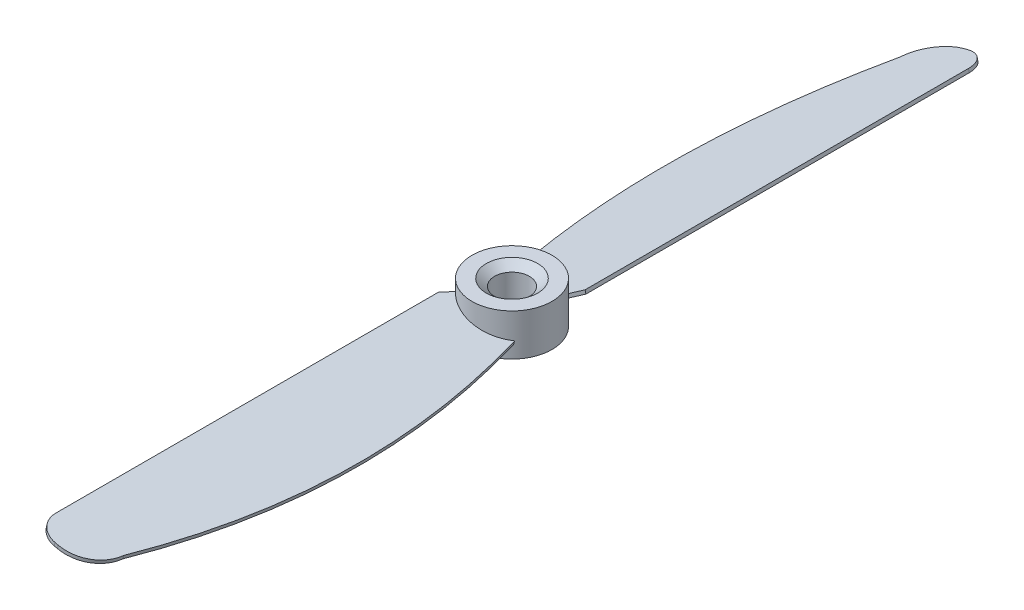
SolidWorks part; units mm, degrees
ref_plane "前视基准面" through (0, 0, 0) normal (0, 0, 1) x (1, 0, 0)
ref_plane "上视基准面" through (0, 0, 0) normal (0, 1, 0) x (1, 0, 0)
ref_plane "右视基准面" through (0, 0, 0) normal (1, 0, 0) x (0, 0, -1)
sketch "草图1" plane through (0, 0, 0) normal (0, 1, 0) x (1, 0, 0)
  circle A0 centre (0, 0) radius 5.75
  dimension "D1" = 11.5
extrude "凸台-拉伸1" add sketch "草图1" along normal mid plane 6
sketch "草图2" plane through (0, 0, 0) normal (0, 0, 1) x (1, 0, 0)
  line L0 (-5.75, 1.3275) -> (5.75, -1.3275) construction
  line L1 (-5.75, 3) -> (-5.75, -3) construction
  line L2 (5.75, -3) -> (5.75, 3) construction
  line L3 (-5.75, -3) -> (5.75, -3) construction
  dimension "D1" = 13
ref_plane "基准面1" through (0, 0, 0) normal (-0.225, -0.9744, 0) x (0.9744, -0.225, 0)
sketch "草图3" plane through (0, 0, 0) normal (-0.225, -0.9744, 0) x (0.9744, -0.225, 0)
  line L0 (-3.9164, 3.2954) -> (-5.3139, 5.3896)
  line L1 (-5.3139, 5.3896) -> (-5.3139, 60.5)
  line L2 (-2.3139, 63.5) -> (-1.8298, 63.5)
  arc A0 (-5.3139, 60.5) -> (-2.3139, 63.5) centre (-2.3139, 60.5) cw
  arc A1 (3.1505, 58.9429) -> (-1.8298, 63.5) centre (-1.8298, 58.5) ccw
  ellipse E0 centre (0.6749, 0) end of major axis (0.6749, 5.75) minor radius 5.6026 construction
  spline S0 degree 2 poles (-3.9164, 3.2954) (0.4787, 7.5633) (3.7607, 1.8481) knots 0 0 0 1 1 1
  spline S1 degree 2 poles (3.1505, 58.9429) (11.8161, 30.4937) (3.7607, 1.8481) knots 0 0 0 1 1 1
  dimension "D2" = 3
  dimension "D3" = 5
  dimension "D1" = 63.5
extrude "凸台-拉伸2" add sketch "草图3" along normal mid plane 0.5
pattern_circular "阵列(圆周)1" count 2 over 360 about axis through (0, -3, 0) along (0, 1, 0) of "凸台-拉伸2"
sketch "草图4" plane through (0, -3, 0) normal (0, -1, 0) x (1, 0, 0)
  circle A0 centre (0, 0) radius 2.5
  dimension "D1" = 5
extrude "切除-拉伸1" cut sketch "草图4" against normal through all
chamfer "倒角1" distance 1 angle 50 2 edges at (0, -3, -2.5) (0, 3, -2.5)
